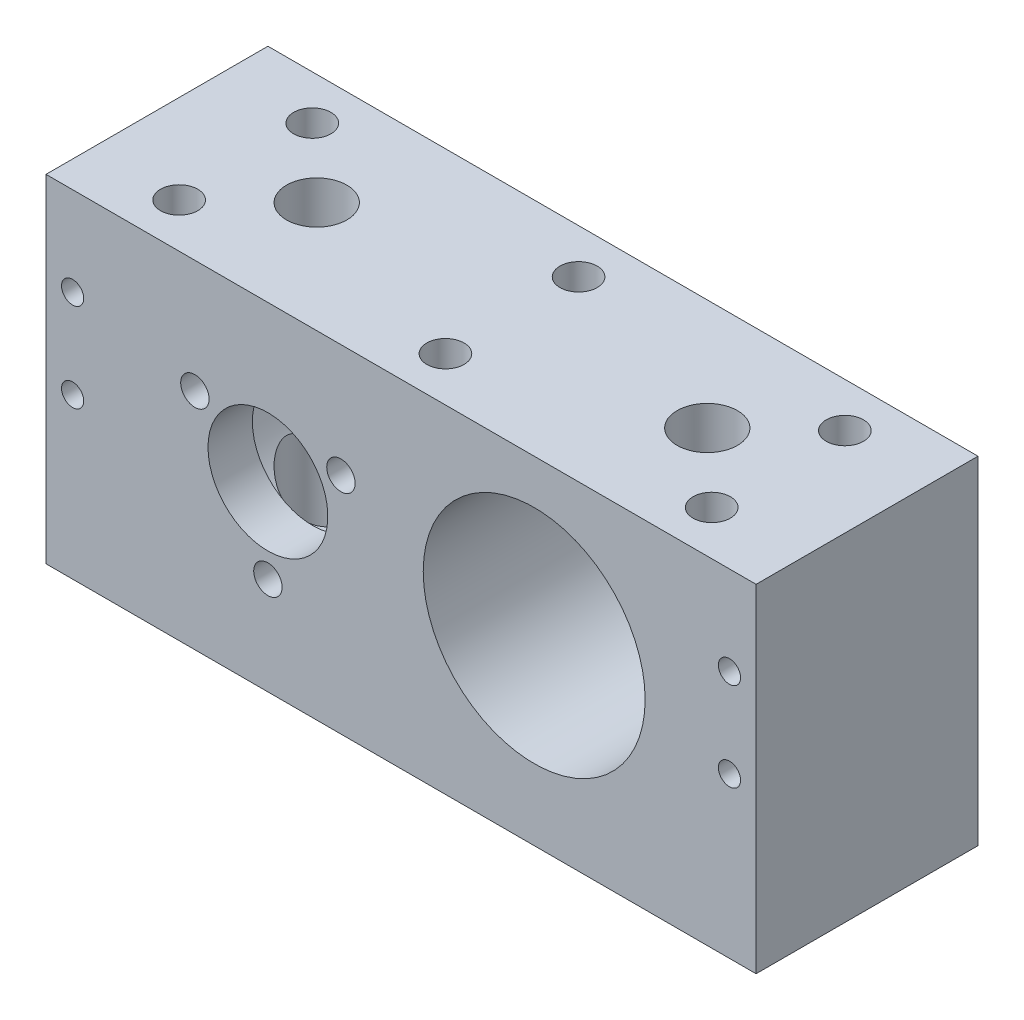
SolidWorks part; units mm, degrees
ref_plane "前视基准面" through (0, 0, 0) normal (0, 0, 1) x (1, 0, 0)
ref_plane "上视基准面" through (0, 0, 0) normal (0, 1, 0) x (1, 0, 0)
ref_plane "右视基准面" through (0, 0, 0) normal (1, 0, 0) x (0, 0, -1)
other "Configuration Table"
sketch "草图1" plane through (0, 0, 0) normal (0, 0, 1) x (1, 0, 0)
  line L1 (-35, 17.5) -> (35, 17.5)
  line L2 (-35, 17.5) -> (-35, -17.5)
  line L3 (-35, -17.5) -> (35, -17.5)
  line L4 (35, 17.5) -> (35, -17.5)
  line L5 (0, -17.5) -> (0, 17.5) construction
  line L6 (-35, 0) -> (35, 0) construction
  point P0 (0, 0)
  dimension "D1" = 70
  dimension "D2" = 35
extrude "凸台-拉伸1" add sketch "草图1" along normal blind 25
sketch "草图3" plane through (0, 0, 0) normal (0, 0, -1) x (-1, 0, 0)
  line L0 (-35, 0) -> (35, 0) construction
  line L1 (-35, -17.5) -> (-35, 17.5) construction
  line L2 (35, 17.5) -> (35, -17.5) construction
  circle A0 centre (15, 0) radius 12.5
  dimension "D1" = 25
  dimension "D2" = 20
extrude "切除-拉伸2" cut sketch "草图3" against normal blind 20
sketch "草图5" plane through (0, 0, 20) normal (0, 0, -1) x (-1, 0, 0)
  circle A0 centre (15, 0) radius 6.75
  dimension "D1" = 13.5
extrude "切除-拉伸4" cut sketch "草图5" against normal blind 5
sketch "草图6" plane through (0, 0, 20) normal (0, 0, -1) x (-1, 0, 0)
  line L0 (15, 0) -> (15, -9.5) construction
  line L1 (15, 0) -> (15, -9.5) construction
  circle A0 centre (15, 0) radius 9.5 construction
  circle A1 centre (15, -9.5) radius 1.6
  circle A2 centre (6.7728, 4.75) radius 1.6
  circle A3 centre (23.2272, 4.75) radius 1.6
  point P13 (15, 0)
  dimension "D1" = 19
  dimension "D2" = 3.2
  dimension "D3" = 0
  dimension "D4" = 3
extrude "切除-拉伸5" cut sketch "草图6" against normal blind 5
sketch "草图8" plane through (0, 0, 25) normal (0, 0, 1) x (1, 0, 0)
  line L0 (35, 0) -> (-35, 0) construction
  line L1 (35, -17.5) -> (35, 17.5) construction
  line L2 (-35, 17.5) -> (-35, -17.5) construction
  circle A0 centre (15, 0) radius 12.5
  dimension "D1" = 25
  dimension "D2" = 20
extrude "切除-拉伸6" cut sketch "草图8" against normal blind 20
sketch "草图9" plane through (0, 0, 5) normal (0, 0, 1) x (1, 0, 0)
  circle A0 centre (15, 0) radius 6.75
  dimension "D1" = 13.5
extrude "切除-拉伸7" cut sketch "草图9" against normal blind 20
sketch "草图10" plane through (0, 0, 5) normal (0, 0, 1) x (1, 0, 0)
  line L0 (15, 0) -> (24.5, 0) construction
  line L1 (15, 0) -> (15, -9.5) construction
  circle A0 centre (15, 0) radius 9.5 construction
  circle A1 centre (15, -9.5) radius 1.6
  circle A2 centre (6.7728, 4.75) radius 1.6
  circle A3 centre (23.2272, 4.75) radius 1.6
  point P12 (15, 0)
  dimension "D1" = 19
  dimension "D3" = 3.2
  dimension "D2" = 90
  dimension "D4" = 3
extrude "切除-拉伸8" cut sketch "草图10" against normal through all
sketch "草图11" plane through (0, -17.5, 0) normal (0, -1, 0) x (1, 0, 0)
  line L0 (35, 12.5) -> (-35, 12.5) construction
  line L1 (35, 25) -> (35, 0) construction
  line L2 (-35, 25) -> (-35, 0) construction
  line L3 (0, 25) -> (0, 0) construction
  line L4 (-35, 25) -> (35, 25) construction
  circle A0 centre (22, 12.5) radius 3.4
  circle A2 centre (-22, 12.5) radius 3.4
  circle A3 centre (0, 12.5) radius 30 construction
  dimension "D1" = 6.8
  dimension "D2" = 22
  dimension "D3" = 60
extrude "切除-拉伸9" cut sketch "草图11" against normal through all
sketch "草图13" plane through (0, -17.5, 0) normal (0, -1, 0) x (1, 0, 0)
  line L1 (35, 25) -> (-35, 25)
  line L2 (35, 25) -> (35, 0)
  line L3 (35, 0) -> (-35, 0)
  line L4 (-35, 25) -> (-35, 0)
  circle A0 centre (-22, 12.5) radius 3.4 construction
  circle A1 centre (22, 12.5) radius 3.4 construction
  circle A2 centre (-22, 12.5) radius 3.4
  circle A3 centre (22, 12.5) radius 3.4
extrude "凸台-拉伸3" add sketch "草图13" along normal blind 3
sketch "草图2" plane through (0, 17.5, 0) normal (0, 1, 0) x (1, 0, 0)
  line L0 (0, 0) -> (0, -25) construction
  line L1 (35, -25) -> (-35, -25) construction
  line L3 (30, -5) -> (-30, -5) construction
  line L4 (30, -5) -> (30, -20) construction
  line L5 (30, -20) -> (-30, -20) construction
  line L6 (-30, -5) -> (-30, -20) construction
  line L7 (0, -20) -> (0, -5) construction
  line L8 (30, -12.5) -> (-30, -12.5) construction
  circle A0 centre (30, -5) radius 2.1
  circle A1 centre (30, -20) radius 2.1
  circle A2 centre (-30, -5) radius 2.1
  circle A3 centre (-30, -20) radius 2.1
  point P5 (0, -12.5)
  dimension "D3" = 4.2
  dimension "D1" = 60
  dimension "D2" = 15
extrude "切除-拉伸1" cut sketch "草图2" against normal through all
sketch "草图15" plane through (-35, 0, 0) normal (-1, 0, 0) x (0, 0, 1)
  line L4 (0, 17.5) -> (0, -20.5)
  line L5 (0, -20.5) -> (25, -20.5)
  line L6 (25, -20.5) -> (25, 17.5)
  line L7 (25, 17.5) -> (0, 17.5)
  line L8 (0, 17.5) -> (0, -20.5)
  line L9 (0, -20.5) -> (25, -20.5)
  line L10 (25, -20.5) -> (25, 17.5)
  line L11 (25, 17.5) -> (0, 17.5)
  dimension "D1" = 0
extrude "凸台-拉伸4" add sketch "草图15" along normal blind 5
sketch "草图16" plane through (35, 0, 0) normal (1, 0, 0) x (0, 0, -1)
  line L4 (0, -20.5) -> (0, 17.5)
  line L5 (0, 17.5) -> (-25, 17.5)
  line L6 (-25, 17.5) -> (-25, -20.5)
  line L7 (-25, -20.5) -> (0, -20.5)
  line L8 (0, -20.5) -> (0, 17.5)
  line L9 (0, 17.5) -> (-25, 17.5)
  line L10 (-25, 17.5) -> (-25, -20.5)
  line L11 (-25, -20.5) -> (0, -20.5)
  dimension "D1" = 0
extrude "凸台-拉伸5" add sketch "草图16" along normal blind 5
sketch "草图17" plane through (0, -20.5, 0) normal (0, -1, 0) x (1, 0, 0)
  line L0 (0, 25) -> (0, 0) construction
  line L1 (40, 25) -> (-40, 25) construction
  line L2 (-40, 0) -> (40, 0) construction
  line L3 (-40, 12.5) -> (40, 12.5) construction
  line L4 (-40, 0) -> (-40, 25) construction
  line L5 (40, 25) -> (40, 0) construction
  circle A1 centre (0, 5) radius 2.1
  circle A2 centre (0, 20) radius 2.1
  dimension "D1" = 4.2
  dimension "D2" = 5
extrude "切除-拉伸11" cut sketch "草图17" against normal through all
sketch "草图18" plane through (0, 0, 0) normal (0, 0, -1) x (-1, 0, 0)
  line L0 (-37, -20.5) -> (-37, 17.5) construction
  line L1 (40, -20.5) -> (-40, -20.5) construction
  line L2 (-40, 17.5) -> (40, 17.5) construction
  line L3 (-40, -20.5) -> (-40, 17.5) construction
  circle A0 centre (-37, 7.5) radius 1.25
  circle A1 centre (-37, -2.5) radius 1.25
  dimension "D4" = 2.5
  dimension "D5" = 2.5
  dimension "D1" = 3
  dimension "D2" = 10
  dimension "D3" = 10
extrude "切除-拉伸12" cut sketch "草图18" against normal blind 5
ref_plane "基准面1" through (0, 0, 12.5) normal (0, 0, 1) x (1, 0, 0)
mirror "镜向1" about plane through (0, 0, 12.5) normal (0, 0, 1) of "切除-拉伸12"
mirror "镜向2" about plane through (0, 0, 0) normal (1, 0, 0) of "镜向1", "切除-拉伸12"
